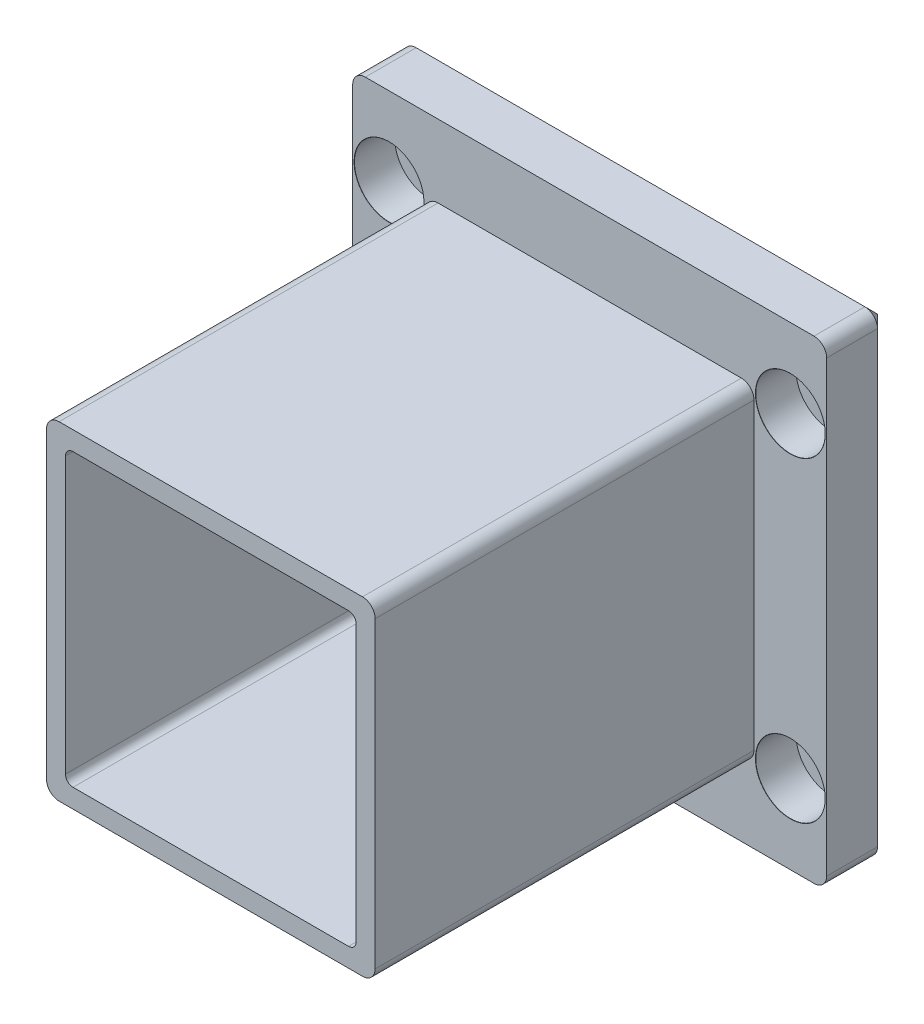
SolidWorks part; units mm, degrees
ref_plane "Front Plane" through (0, 0, 0) normal (1, 0, 0) x (0, 1, 0)
ref_plane "Top Plane" through (0, 0, 0) normal (0, 0, 1) x (0, 1, 0)
ref_plane "Right Plane" through (0, 0, 0) normal (0, 1, 0) x (-1, 0, 0)
sketch "Sketch1" plane through (0, 0, 0) normal (0, 0, 1) x (0, 1, 0)
  line L0 (-29.048, 30.1461) -> (-26.1566, 30.1461)
  line L1 (-29.048, 30.1461) -> (22.952, 30.1461)
  line L2 (-29.048, 30.1461) -> (-29.048, -21.8539)
  line L3 (-29.048, -21.8539) -> (22.952, -21.8539)
  line L4 (22.952, 30.1461) -> (22.952, -21.8539)
  line L6 (22.952, 30.1461) -> (15.3397, 30.1461)
  line L8 (-26.048, 27.1461) -> (-26.048, -18.8539)
  line L9 (-26.048, -18.8539) -> (19.952, -18.8539)
  line L10 (19.952, 27.1461) -> (19.952, -18.8539)
  line L11 (-26.048, 27.1461) -> (19.952, 27.1461)
  dimension "D1" = 46
  dimension "D2" = 46
  dimension "D3" = 3
extrude "Boss-Extrude1" add sketch "Sketch1" along normal blind 65 contours L4 L1 L0 L2 L3 L8 L11 L10 L9
sketch "Sketch3" plane through (0, 0, 0) normal (0, 0, -1) x (1, 0, 0)
  line L0 (-4.1461, 29.048) -> (-4.1461, -22.952)
  line L1 (-30.1461, 29.048) -> (21.8539, 29.048) construction
  line L2 (-30.1461, -22.952) -> (21.8539, -22.952) construction
  line L3 (21.8539, 29.048) -> (33.3539, 40.548)
  line L4 (-41.6461, 40.548) -> (33.3539, 40.548)
  line L5 (-41.6461, 40.548) -> (-41.6461, -34.452)
  line L6 (-41.6461, -34.452) -> (33.3539, -34.452)
  line L7 (33.3539, 40.548) -> (33.3539, -34.452)
  line L8 (-41.6461, 40.548) -> (33.3539, -34.452) construction
  line L9 (-41.6461, -34.452) -> (33.3539, 40.548) construction
  line L10 (27.6039, -21.952) -> (27.6039, 28.048)
  line L11 (27.6039, -28.702) -> (27.6039, 34.798)
  line L12 (-29.1461, 34.798) -> (20.8539, 34.798)
  line L13 (-35.8961, -21.952) -> (-35.8961, 28.048)
  line L14 (20.8539, -28.702) -> (-29.1461, -28.702)
  point P6 (-4.1461, 3.048)
  point P22 (27.6039, 3.048)
  line M5 (-30.1461, -22.952) -> (21.8539, -22.952)
  line M6 (21.8539, -22.952) -> (21.8539, 29.048)
  line M7 (21.8539, 29.048) -> (-30.1461, 29.048)
  line M8 (-30.1461, 29.048) -> (-30.1461, -22.952)
  line M9 (-27.1461, 26.048) -> (18.8539, 26.048)
  line M10 (18.8539, 26.048) -> (18.8539, -19.952)
  line M11 (18.8539, -19.952) -> (-27.1461, -19.952)
  line M12 (-27.1461, -19.952) -> (-27.1461, 26.048)
  dimension "D1" = 50
  dimension "D2" = 75
extrude "Boss-Extrude2" add sketch "Sketch3" along normal blind 5 contours L0 M9 M12 M11 | L0 M9 M11 M10 | L0 M7 M8 M5 M11 M12 M9 | L0 M7 M9 M10 M11 M5 M6 | L7 L4 L5 L6 M5 M8 M7 M6
sketch "Sketch8" plane through (0, 0, 0) normal (0, 0, 1) x (1, 0, 0)
  line L1 (-41.6461, 34.452) -> (33.3539, 34.452)
  line L2 (-41.6461, 34.452) -> (-41.6461, -40.548)
  line L3 (-41.6461, -40.548) -> (33.3539, -40.548)
  line L4 (33.3539, 34.452) -> (33.3539, -40.548)
  line L5 (-30.1461, 22.952) -> (21.8539, 22.952)
  line L6 (-30.1461, 22.952) -> (-30.1461, -29.048)
  line L7 (-30.1461, -29.048) -> (21.8539, -29.048)
  line L8 (21.8539, 22.952) -> (21.8539, -29.048)
extrude "Boss-Extrude3" add sketch "Sketch8" along normal blind 5.0471
fillet "Fillet1" radius 2 8 edges at (21.8539, -29.048, 35.0235) (-30.1461, -29.048, 35.0235) (-30.1461, 22.952, 35.0235) (21.8539, 22.952, 35.0235) (33.3539, 34.452, 0.0235) (-41.6461, 34.452, 0.0235) (-41.6461, -40.548, 0.0235) (33.3539, -40.548, 0.0235)
sketch "Sketch13" plane through (0, 0, 5.0471) normal (0, 0, 1) x (1, 0, 0)
  line L0 (-35.8961, 21.952) -> (-35.8961, -28.048)
  line L1 (-29.1461, -34.798) -> (20.8539, -34.798)
  line L2 (-41.6461, 34.452) -> (33.3539, -40.548)
  line L3 (27.6039, 21.952) -> (27.6039, -28.048)
  line L4 (-29.1461, 28.702) -> (20.8539, 28.702)
  point P0 (-35.8961, 21.952)
  point P1 (-35.8961, -28.048)
  point P12 (27.6039, 21.952)
  point P13 (27.6039, -28.048)
hole_wizard "CBORE for M6 Hex Socket Head Cap Screw2" positions "Sketch13" profile "Sketch15" counterbore size "M6" standard "ISO" end condition through all
sketch "Sketch15" plane through (-35.8961, 21.952, 5.0471) normal (1, 0, 0) x (0, -1, 0)
  line L0 (0, 0) -> (0, 10.0471)
  line L1 (0, 10.0471) -> (3.3, 10.0471)
  line L3 (3.3, 10.0471) -> (3.3, 6.4)
  line L4 (5.5, 6.4) -> (3.3, 6.4)
  line L5 (5.5, 6.4) -> (5.5, 0.025)
  line L6 (5.5, 0.025) -> (5.525, 0)
  line L7 (5.525, 0) -> (0, 0)
  line L8 (-5.5, 0.025) -> (-5.525, 0) construction
  line L11 (0, -6.35) -> (0, 107.95) construction
  dimension "Thru Hole Dia." = 6.6
  dimension "Thru Hole Depth" = 10.0471
  dimension "C'Bore Dia." = 11
  dimension "C'Bore Depth" = 6.4
  dimension "Near C'Sink Dia." = 11.05
  dimension "Near C'Sink Angle" = 90
chamfer "Chamfer2" distance 2 angle 45 8 edges at (-41.6461, -3.048, -5) (-4.1461, -40.548, -5) (33.3539, -3.048, -5) (-41.0603, -39.9622, -5) (32.7681, -39.9622, -5) (-41.0603, 33.8662, -5) (32.7681, 33.8662, -5) (-4.1461, 34.452, -5)
fillet "Fillet2" radius 1.2 4 edges at (18.8539, 19.952, 32.5) (-27.1461, 19.952, 32.5) (-27.1461, -26.048, 32.5) (18.8539, -26.048, 32.5)
